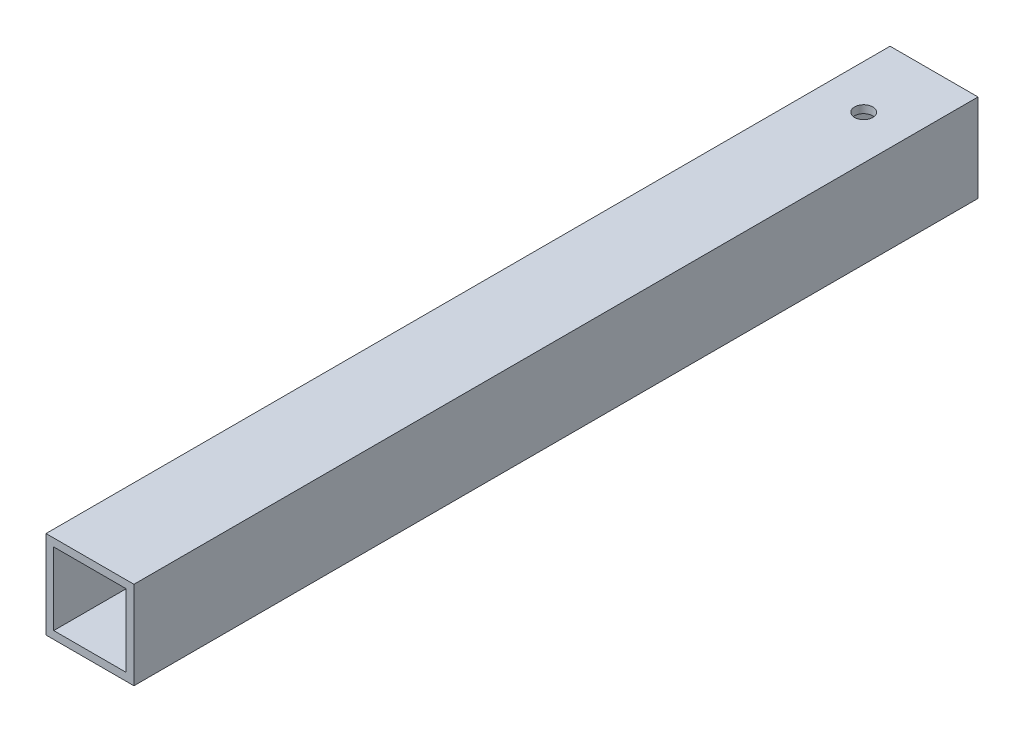
SolidWorks part; units mm, degrees
material "6061-T6 (SS)"
ref_plane "Front Plane" through (0, 0, 0) normal (0, 0, 1) x (1, 0, 0)
ref_plane "Top Plane" through (0, 0, 0) normal (0, 1, 0) x (1, 0, 0)
ref_plane "Right Plane" through (0, 0, 0) normal (1, 0, 0) x (0, 0, -1)
sketch "Sketch1" plane through (0, 0, 0) normal (0, 0, 1) x (1, 0, 0)
  line L0 (13.081, 13.081) -> (-13.081, 13.081)
  line L1 (15.875, -15.875) -> (-15.875, -15.875)
  line L2 (15.875, -15.875) -> (15.875, 15.875)
  line L3 (15.875, 15.875) -> (-15.875, 15.875)
  line L4 (-15.875, -15.875) -> (-15.875, 15.875)
  line L5 (15.875, -15.875) -> (-15.875, 15.875) construction
  line L6 (15.875, 15.875) -> (-15.875, -15.875) construction
  line L7 (-13.081, -13.081) -> (-13.081, 13.081)
  line L8 (13.081, -13.081) -> (-13.081, -13.081)
  line L9 (13.081, -13.081) -> (13.081, 13.081)
  point P0 (0, 0)
  dimension "D1" = 31.75
  dimension "D2" = 2.794
extrude "Boss-Extrude1" add sketch "Sketch1" along normal blind 304.8
sketch "Sketch2" plane through (0, 15.875, 0) normal (0, 1, 0) x (1, 0, 0)
  line L0 (15.875, 0) -> (-15.875, 0) construction
  circle A0 centre (0, -25.4) radius 3.302
  dimension "D1" = 6.604
  dimension "D2" = 25.4
extrude "Cut-Extrude1" cut sketch "Sketch2" against normal through all
